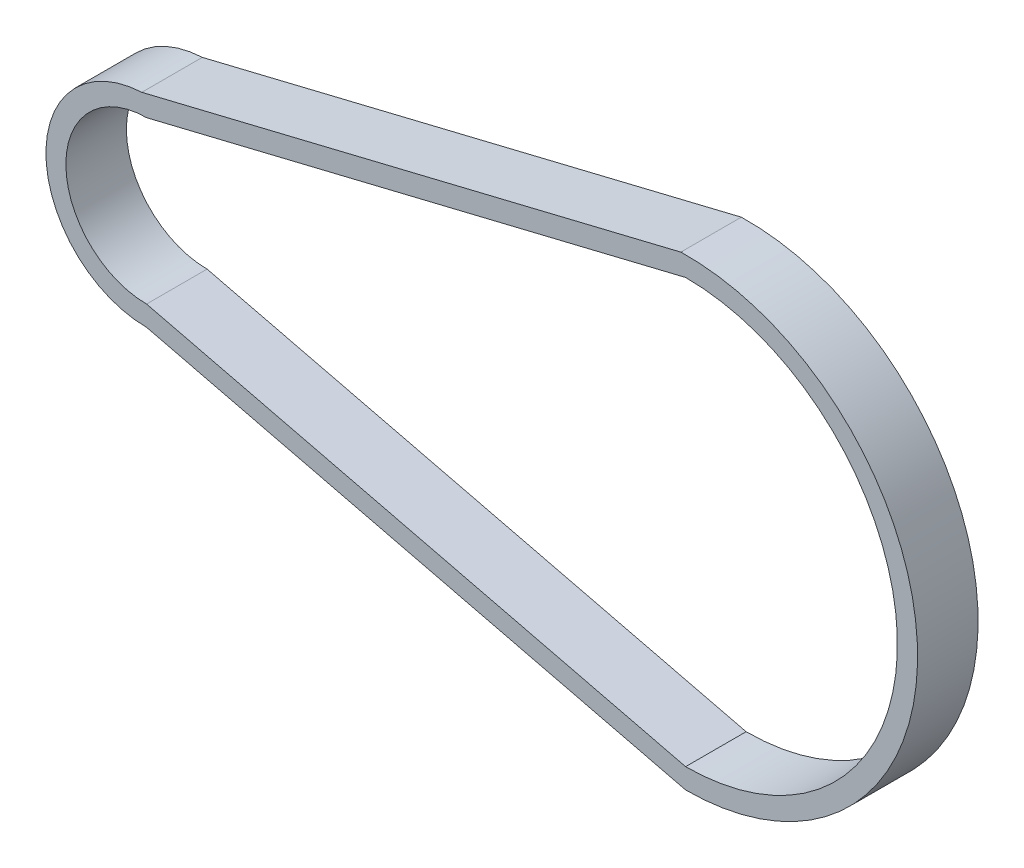
SolidWorks part; units mm, degrees
ref_plane "Front Plane" through (0, 0, 0) normal (0, 0, 1) x (1, 0, 0)
ref_plane "Top Plane" through (0, 0, 0) normal (0, 1, 0) x (1, 0, 0)
ref_plane "Right Plane" through (0, 0, 0) normal (1, 0, 0) x (0, 0, -1)
sketch "Sketch1" plane through (0, 0, 0) normal (0, 0, 1) x (1, 0, 0)
  line L0 (0, 0) -> (-53.4416, 0) construction
  line L1 (0, 21) -> (-53.4416, 8)
  line L2 (0, -21) -> (-53.4416, -8)
  line L3 (-0.4727, 22.9433) -> (-53.9143, 9.9433)
  line L4 (-53.4416, -10) -> (0, -23)
  line L5 (0, 0) -> (21, 0)
  line L6 (21, 0) -> (23, 0)
  circle A0 centre (0, 0) radius 21 construction
  circle A1 centre (-53.4416, 0) radius 8 construction
  circle A2 centre (-53.4416, 0) radius 10 construction
  circle A3 centre (0, 0) radius 23 construction
  arc A4 (-53.4416, 8) -> (-53.4416, -8) centre (-53.4416, 0) ccw
  arc A5 (-53.9143, 9.9433) -> (-53.4416, -10) centre (-53.4416, -0.0227) ccw
  arc A6 (-0.4727, 22.9433) -> (0, -23) centre (0.0256, -0.0256) cw
  arc A7 (0, 21) -> (0, -21) centre (0, 0) cw
  dimension "D1" = 42
  dimension "D2" = 2
  dimension "16" = 16
  dimension "D3" = 55
extrude "Boss-Extrude1" add sketch "Sketch1" along normal blind 6
